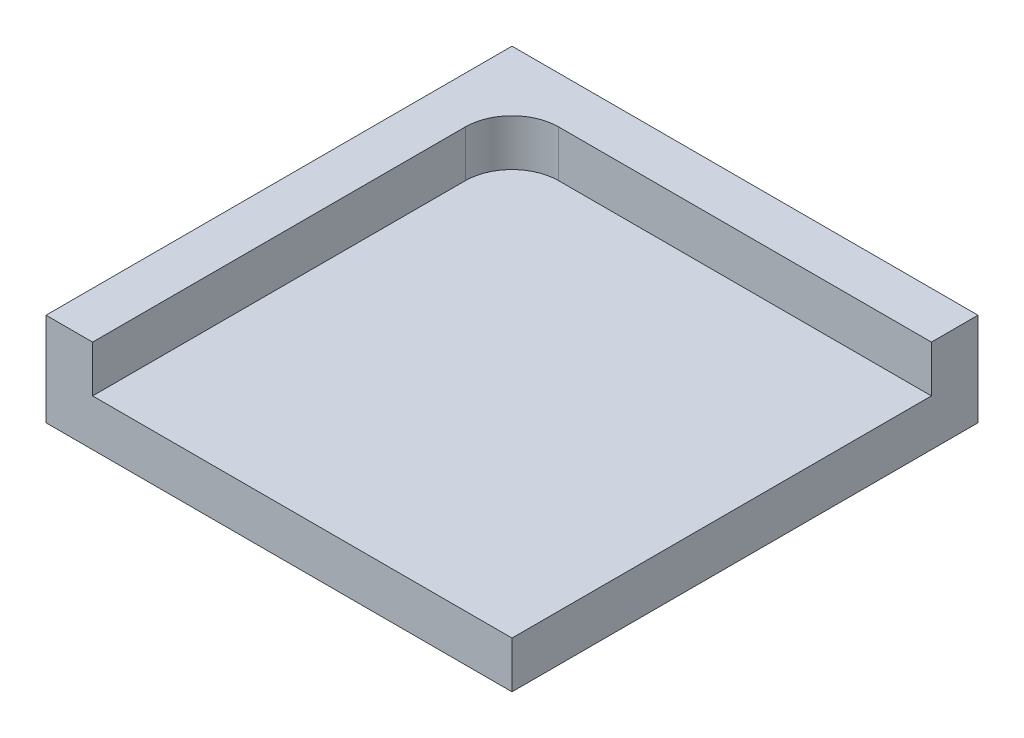
SolidWorks part; units mm, degrees
ref_plane "Front Plane" through (0, 0, 0) normal (0, 0, 1) x (1, 0, 0)
ref_plane "Top Plane" through (0, 0, 0) normal (0, 1, 0) x (1, 0, 0)
ref_plane "Right Plane" through (0, 0, 0) normal (1, 0, 0) x (0, 0, -1)
sketch "Sketch1" plane through (0, 0, 0) normal (0, 1, 0) x (1, 0, 0)
  line L1 (-10, -10) -> (10, -10)
  line L2 (-10, -10) -> (-10, 10)
  line L3 (-10, 10) -> (10, 10)
  line L4 (10, -10) -> (10, 10)
  line L5 (-10, -10) -> (10, 10) construction
  line L6 (-10, 10) -> (10, -10) construction
  point P0 (0, 0)
  dimension "D1" = 20
  dimension "D2" = 20
extrude "Boss-Extrude2" add sketch "Sketch1" against normal blind 2
sketch "Sketch2" plane through (0, 0, 0) normal (0, 1, 0) x (1, 0, 0)
  line L0 (0, 0) -> (-10, 0) construction
  line L1 (-10, 10) -> (-10, -10) construction
  line L2 (-8, -10) -> (-8, 10) construction
  line L3 (10, 10) -> (-10, 10) construction
  line L4 (0, 0) -> (0, 10) construction
  line L5 (-10, 8) -> (10, 8) construction
  line L6 (10, -10) -> (10, 10) construction
  line L7 (-6, 8) -> (10, 8)
  line L8 (-8, 6) -> (-8, -10)
  line L9 (-8, -10) -> (-10, -10)
  line L10 (-10, -10) -> (-10, 10)
  line L11 (-10, 10) -> (10, 10)
  line L12 (10, 10) -> (10, 8)
  arc A0 (-8, 6) -> (-6, 8) centre (-6, 6) cw
  point P5 (-8, 8)
  point P10 (-8, 0)
  point P16 (0, 8)
  point P20 (-8, 8)
  dimension "D3" = 2
  dimension "D1" = 2
  dimension "D2" = 2
extrude "Boss-Extrude3" add sketch "Sketch2" along normal blind 2 contours L12 L7 A0 L8 L9 L10 L11
